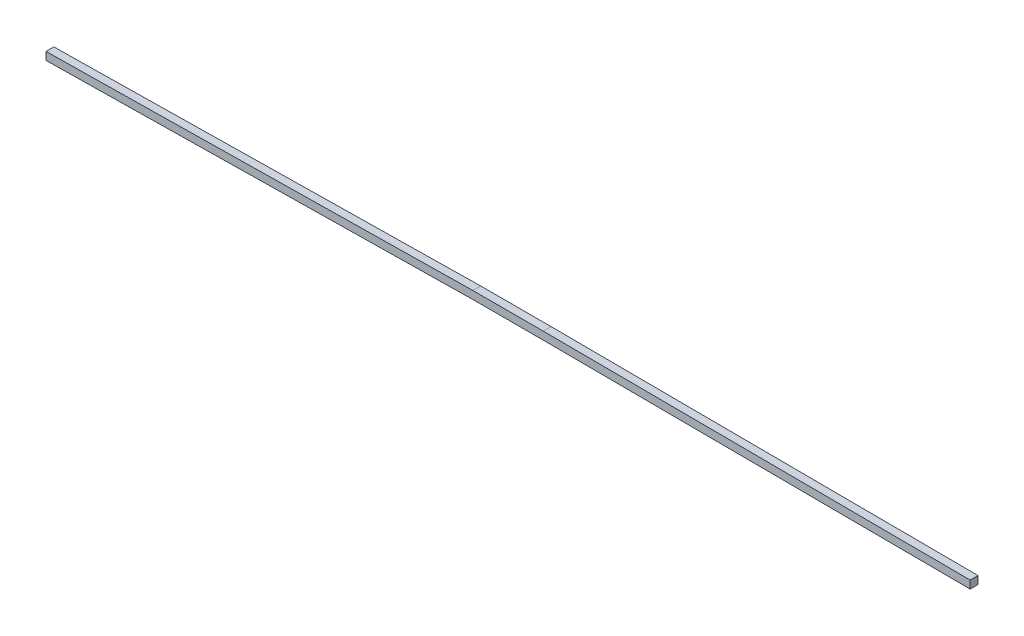
SolidWorks part; units mm, degrees
ref_plane "前视基准面" through (0, 0, 0) normal (0, 0, 1) x (1, 0, 0)
ref_plane "上视基准面" through (0, 0, 0) normal (0, 1, 0) x (1, 0, 0)
ref_plane "右视基准面" through (0, 0, 0) normal (1, 0, 0) x (0, 0, -1)
sketch "Model" plane through (0, 0, 0) normal (0, 0, 1) x (1, 0, 0)
  line L0 (775.8163, 179.2795) -> (503.22, 180.6395)
  line L1 (503.22, 180.6395) -> (458.22, 180.6395)
  line L2 (185.6508, 176.5596) -> (458.22, 180.6395)
  line L3 (185.6508, 176.5596) -> (185.6508, 171.5596)
  line L4 (185.6508, 171.5596) -> (458.2948, 175.64)
  line L5 (458.2948, 175.64) -> (503.2948, 175.64)
  line L6 (775.8163, 179.2795) -> (775.8163, 174.2795)
  line L7 (775.8163, 174.2795) -> (503.2948, 175.64)
extrude "凸台-拉伸1" add sketch "Model" along normal blind 5
